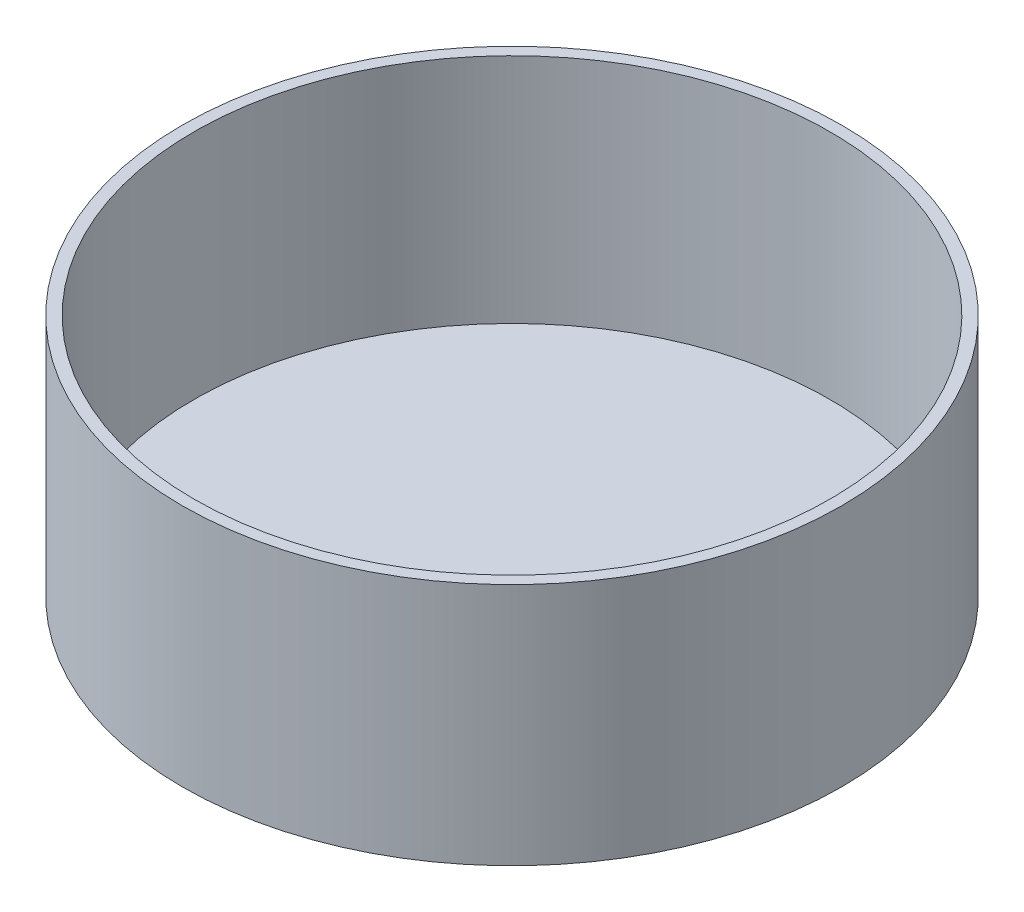
SolidWorks part; units mm, degrees
ref_plane "Front Plane" through (0, 0, 0) normal (0, 0, 1) x (1, 0, 0)
ref_plane "Top Plane" through (0, 0, 0) normal (0, 1, 0) x (1, 0, 0)
ref_plane "Right Plane" through (0, 0, 0) normal (1, 0, 0) x (0, 0, -1)
sketch "Sketch1" plane through (0, 0, 0) normal (0, 1, 0) x (1, 0, 0)
  circle A0 centre (0, 0) radius 54.875 construction
  circle A1 centre (0, 0) radius 56.875
  dimension "D1" = 2
  dimension "D2" = 109.75
extrude "Boss-Extrude1" add sketch "Sketch1" along normal blind 2
sketch "Sketch2" plane through (0, 2, 0) normal (0, 1, 0) x (1, 0, 0)
  circle A0 centre (0, 0) radius 54.875
  circle A1 centre (0, 0) radius 56.875
  circle A2 centre (0, 0) radius 56.875 construction
  circle A3 centre (0, 0) radius 54.875 construction
extrude "Boss-Extrude2" add sketch "Sketch2" along normal blind 40
